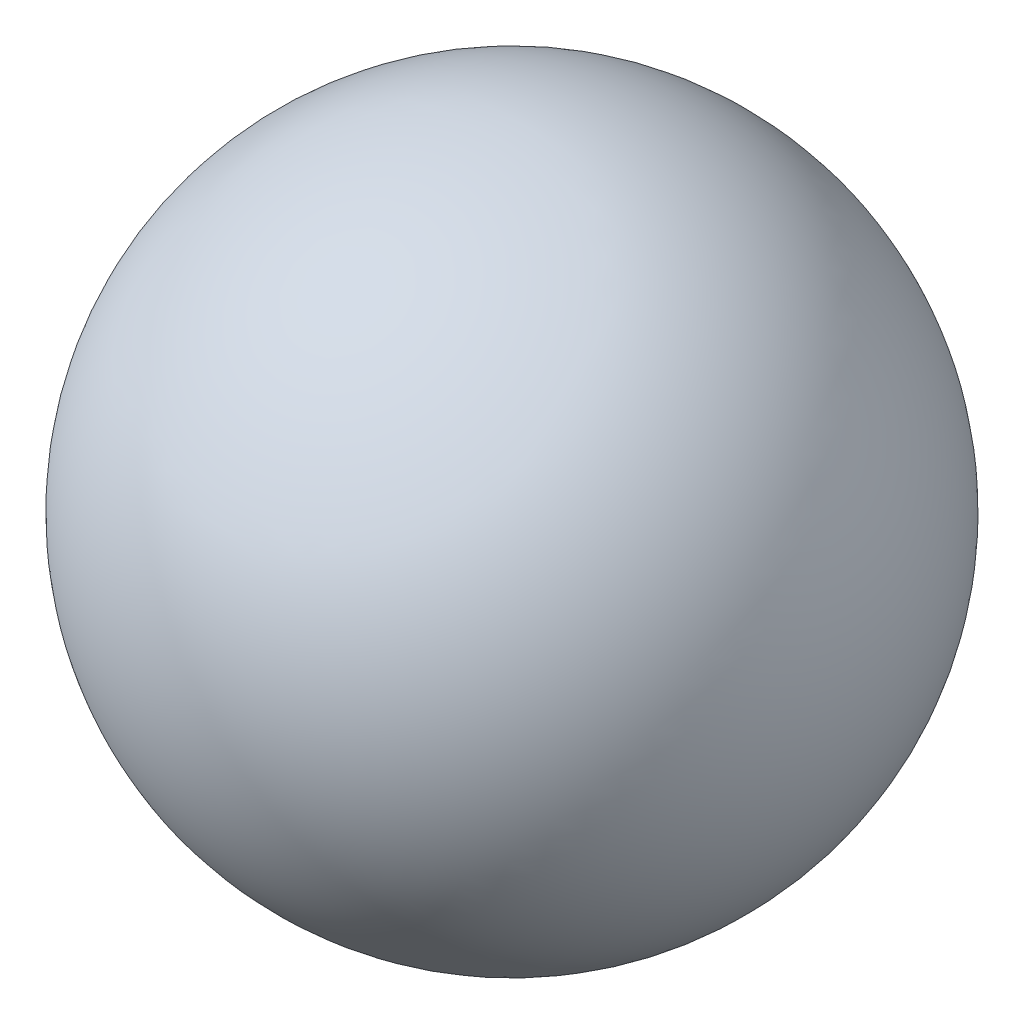
SolidWorks part; units mm, degrees
ref_plane "Front Plane" through (0, 0, 0) normal (0, 0, 1) x (1, 0, 0)
ref_plane "Top Plane" through (0, 0, 0) normal (0, 1, 0) x (1, 0, 0)
ref_plane "Right Plane" through (0, 0, 0) normal (1, 0, 0) x (0, 0, -1)
sketch "Sketch1" plane through (0, 0, 0) normal (1, 0, 0) x (0, 0, -1)
  line L0 (-33.7126, 0) -> (45.7039, 0) construction
  line L2 (-19, 0) -> (-18.5, 0)
  line L3 (18.5, 0) -> (19, 0)
  arc A0 (19, 0) -> (-19, 0) centre (0, 0) ccw
  arc A1 (18.5, 0) -> (-18.5, 0) centre (0, 0) ccw
  dimension "D1" = 38
  dimension "D2" = 37
revolve "Revolve5" add sketch "Sketch1" angle 360 about L0
